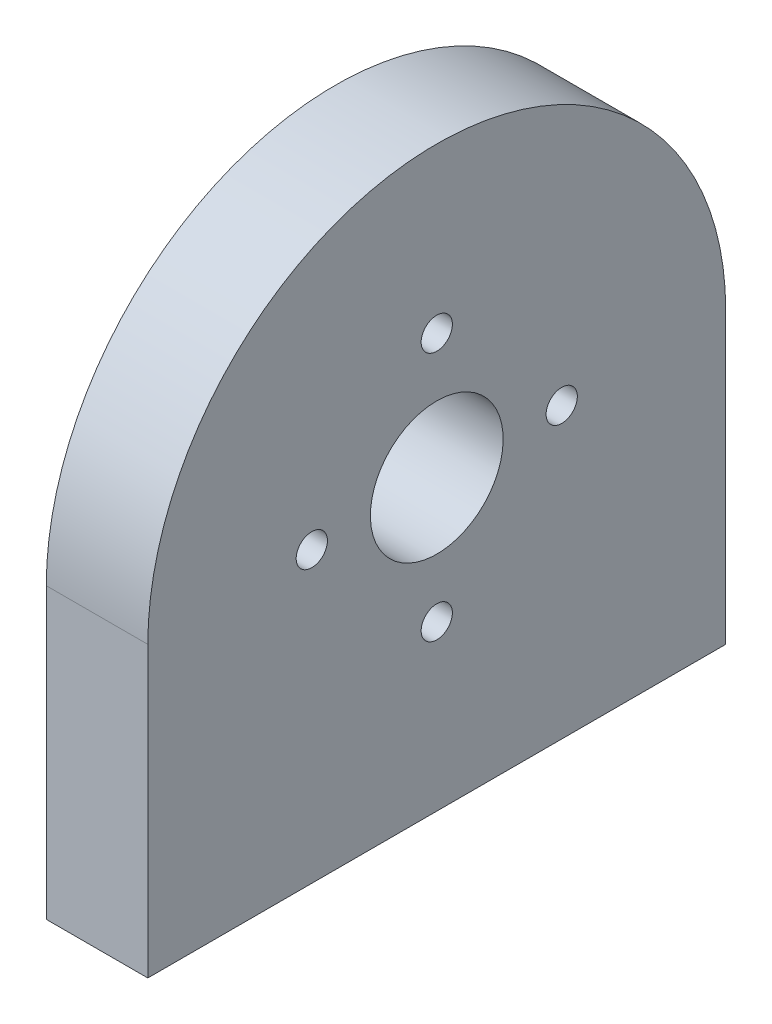
SolidWorks part; units mm, degrees
ref_plane "Front Plane" through (0, 0, 0) normal (0, 0, 1) x (1, 0, 0)
ref_plane "Top Plane" through (0, 0, 0) normal (0, 1, 0) x (1, 0, 0)
ref_plane "Right Plane" through (0, 0, 0) normal (1, 0, 0) x (0, 0, -1)
sketch "Sketch1" plane through (0, 0, 0) normal (0, 0, 1) x (1, 0, 0)
  line L1 (-25, 0) -> (25, 0)
  line L2 (-25, 0) -> (-25, -150)
  line L3 (-25, -150) -> (25, -150)
  line L4 (25, 0) -> (25, -150)
  dimension "D1" = 50
  dimension "D2" = 150
extrude "Boss-Extrude1" add sketch "Sketch1" against normal blind 55
sketch "Sketch2" plane through (25, 0, 0) normal (1, 0, 0) x (0, 0, -1)
  line L0 (55, 0) -> (0, 0) construction
  line L1 (0, -150) -> (0, 0) construction
  circle A0 centre (27.5, -25) radius 10.25
  dimension "D1" = 25
  dimension "D2" = 27.5
extrude "Cut-Extrude1" cut sketch "Sketch2" against normal blind 45 and the other way through all
sketch "Sketch7" plane through (-20, 0, 0) normal (1, 0, 0) x (0, 0, -1)
  line L0 (27.5, -17) -> (27.5, -33) construction
  circle A0 centre (27.5, -25) radius 8
  circle A1 centre (27.5, -17) radius 1
  circle A2 centre (35.5, -25) radius 1
  circle A3 centre (27.5, -33) radius 1
  circle A4 centre (19.5, -25) radius 1
  circle A5 centre (27.5, -25) radius 4.25
  point P14 (27.5, -25)
  dimension "D1" = 16
  dimension "D2" = 2
  dimension "D4" = 8.5
  dimension "D3" = 4
extrude "Cut-Extrude3" cut sketch "Sketch7" against normal blind 10 contours L0 A0 A1 | A0 A1 | A0 L0 A1 | A0 A4 | A0 A4 | L0 A3 A0 | A3 L0 A0 | A0 A3 | A0 A2 | A0 A2 | A5 L0 | L0 A5
sketch "Sketch8" plane through (25, 0, 0) normal (1, 0, 0) x (0, 0, -1)
  line L1 (55, -150) -> (55, 0) construction
  line L3 (0, -150) -> (55, -150)
  line L4 (0, -150) -> (0, -205)
  line L5 (0, -205) -> (55, -205)
  line L6 (55, -150) -> (55, -205)
  circle A1 centre (27.5, -180) radius 10.25
  circle A3 centre (27.5, -25) radius 10.25 construction
  dimension "D1" = 27.5
  dimension "D2" = 155
  dimension "D3" = 25
extrude "Boss-Extrude2" add sketch "Sketch8" against normal blind 50
sketch "Sketch10" plane through (0, 0, 0) normal (0, 0, 1) x (1, 0, 0)
  line L0 (-25, -205) -> (25, -205) construction
  line L5 (17, -205) -> (-17, -205)
  line L6 (17, -205) -> (17, -144.75)
  line L8 (-17, -205) -> (-17, -144.75)
  line L9 (-25, 0) -> (-25, -205) construction
  line L10 (-25, -180) -> (25, -180)
  line L13 (25, -169.75) -> (-25, -169.75)
  line L14 (25, -169.75) -> (25, -190.25)
  line L15 (25, -190.25) -> (-25, -190.25)
  line L16 (-25, -169.75) -> (-25, -190.25)
  line L17 (25, -205) -> (25, 0) construction
  line L18 (0, -180) -> (17, -180)
  line L19 (0, -180) -> (0, -191.25)
  line L20 (0, -191.25) -> (17, -191.25)
  line L21 (17, -180) -> (17, -191.25)
  line L22 (17, -191.25) -> (-17, -191.25)
  line L23 (17, -191.25) -> (17, -169.75)
  line L24 (17, -169.75) -> (-17, -169.75)
  line L25 (-17, -191.25) -> (-17, -169.75)
  line L26 (17, -191.25) -> (-17, -191.25)
  line L27 (17, -191.25) -> (17, -144.75)
  line L28 (17, -144.75) -> (-17, -144.75)
  line L29 (-17, -191.25) -> (-17, -144.75)
  line L30 (-25, -169.75) -> (-17, -169.75)
  line L31 (-25, -169.75) -> (-25, -205)
  line L32 (-25, -205) -> (-17, -205)
  line L33 (-17, -169.75) -> (-17, -205)
  line L34 (25, -169.75) -> (17, -169.75)
  line L35 (25, -169.75) -> (25, -205)
  line L36 (25, -205) -> (17, -205)
  line L37 (17, -169.75) -> (17, -205)
  line L38 (-25, -169.75) -> (25, -169.75)
  line L39 (-25, -169.75) -> (-25, -164.75)
  line L40 (-25, -164.75) -> (25, -164.75)
  line L41 (25, -169.75) -> (25, -164.75)
  line M7 (-25, 0) -> (-25, -205)
  line M8 (-25, -205) -> (25, -205)
  line M9 (25, -205) -> (25, 0)
  dimension "D1" = 8
  dimension "D2" = 8
  dimension "D3" = 11.25
  dimension "D4" = 46.5
  dimension "D5" = 60.25
  dimension "D6" = 5
extrude "Cut-Extrude4" cut sketch "Sketch10" against normal through all contours L20 L22 L8 L6 M8 | L8 L15 M7 M8 | L15 L6 M9 M8 | L15 L8 L10 M7 | L8 L13 L10 M7 | L13 L6 L10 M9 | L15 L10 L6 M9 | L19 L10 L8 L15 | L10 L19 L15 L6 | L6 L13 L8 L10 | L22 L19 L15 L8 | L19 L20 L6 L15 | L29 L40 L27 L28 | L40 L8 L13 L6
sketch "Sketch11" plane through (0, -144.75, 0) normal (0, -1, 0) x (1, 0, 0)
  line L0 (17, -55) -> (17, 0) construction
  line L1 (-17, 0) -> (17, 0)
  line L2 (-17, 0) -> (-17, -13.25)
  line L3 (-17, -13.25) -> (17, -13.25)
  line L4 (17, 0) -> (17, -13.25)
  line L5 (25, -27.5) -> (-30.9131, -27.5) construction
  line L6 (25, -55) -> (25, 0) construction
  line L7 (17, -55) -> (17, -41.75)
  line L8 (-17, -41.75) -> (17, -41.75)
  line L9 (-17, -55) -> (-17, -41.75)
  line L10 (-17, -55) -> (17, -55)
  dimension "D1" = 14.25
extrude "Boss-Extrude4" add sketch "Sketch11" along normal blind 25
sketch "Sketch13" plane through (25, 0, 0) normal (1, 0, 0) x (0, 0, -1)
  line L0 (0, -169.75) -> (0, 0) construction
  line L1 (55, -169.75) -> (0, -169.75)
  line L2 (55, -169.75) -> (55, -159.75)
  line L3 (55, -159.75) -> (0, -159.75)
  line L4 (0, -169.75) -> (0, -159.75)
  dimension "D1" = 10
extrude "Cut-Extrude5" cut sketch "Sketch13" against normal blind 8
ref_plane "Plane2" through (0, 0, 0) normal (1, 0, 0) x (0, 0, -1)
mirror "Mirror2" about plane through (0, 0, 0) normal (1, 0, 0) of "Cut-Extrude5"
sketch "Sketch14" plane through (25, 0, 0) normal (1, 0, 0) x (0, 0, -1)
  line L0 (55, -159.75) -> (0, -159.75) construction
  line L1 (0, -159.75) -> (0, 0) construction
  circle A1 centre (16.5, -148) radius 5.0302
  circle A2 centre (38.5, -148) radius 5.0302
  dimension "D1" = 16.5
  dimension "D2" = 2
  dimension "D3" = 11.75
extrude "Cut-Extrude6" cut sketch "Sketch14" against normal blind 8
mirror "Mirror3" about plane through (0, 0, 0) normal (1, 0, 0) of "Cut-Extrude6"
sketch "Sketch15" plane through (0, 0, 0) normal (0, 0, 1) x (1, 0, 0)
  line L0 (-25, 0) -> (25, 0)
  line L1 (25, 0) -> (0, 0)
  line L3 (-17, -169.75) -> (17, -169.75)
  line L4 (-17, -169.75) -> (-17, -170)
  line L5 (-17, -170) -> (17, -170)
  line L6 (17, -169.75) -> (17, -170)
  line M5 (-17, -169.75) -> (17, -169.75)
  dimension "D1" = 0.25
extrude "Boss-Extrude5" add sketch "Sketch15" against normal blind 13.25 contours L6 L4 L5 M5
ref_plane "Plane3" through (0, 0, -27.5) normal (0, 0, 1) x (1, 0, 0)
mirror "Mirror4" about plane through (0, 0, -27.5) normal (0, 0, 1) of "Boss-Extrude5"
sketch "Sketch16" plane through (0, 0, 0) normal (0, 0, 1) x (1, 0, 0)
  line L7 (-20, -14.75) -> (-18.5, -14.75)
  line L8 (-20, -14.75) -> (-20, -35.25)
  line L9 (-20, -35.25) -> (-18.5, -35.25)
  line L10 (-18.5, -14.75) -> (-18.5, -35.25)
  line L11 (25, 0) -> (-18.5, 0)
  line L12 (25, 0) -> (25, -43.5)
  line L13 (25, -43.5) -> (-18.5, -43.5)
  line L14 (-18.5, 0) -> (-18.5, -43.5)
  line M12 (25, -159.75) -> (25, 0)
  line M13 (25, 0) -> (-25, 0)
  dimension "D1" = 1.5
  dimension "D2" = 43.5
  dimension "D3" = 43.5
extrude "Cut-Extrude7" cut sketch "Sketch16" against normal through all contours L14 L10 L13 M13 M12
sketch "Sketch19" plane through (-20, 0, 0) normal (1, 0, 0) x (0, 0, -1)
  circle A0 centre (27.5, -25) radius 4.25
  circle A1 centre (35.5, -25) radius 1
  circle A2 centre (27.5, -33) radius 1
  circle A3 centre (19.5, -25) radius 1
  circle A4 centre (27.5, -17) radius 1
  point P15 (27.5, -25)
  circle M5 centre (27.5, -25) radius 4.25
  circle M6 centre (27.5, -17) radius 1
  circle M7 centre (35.5, -25) radius 1
  circle M8 centre (27.5, -33) radius 1
  circle M9 centre (19.5, -25) radius 1
  circle M10 centre (27.5, -25) radius 10.25
  dimension "D1" = 4
extrude "Boss-Extrude6" add sketch "Sketch19" along normal blind 1.5 contours M10 M6 M8 M9 M7 M5
sketch "Sketch20" plane through (-18.5, 0, 0) normal (1, 0, 0) x (0, 0, -1)
  line L0 (0, -43.5) -> (9, -43.5)
  line L1 (9, -25) -> (9, -43.5)
  line L2 (9, -43.5) -> (0, -43.5)
  line L3 (46, -25) -> (46, -43.5)
  line L4 (46, -43.5) -> (55, -43.5)
  line L5 (46, -43.5) -> (55, -43.5)
  line L7 (9, -43.5) -> (0, -43.5)
  line L8 (9, -43.5) -> (9, -25)
  line L12 (9, -25) -> (9, -43.5)
  line L13 (9, -43.5) -> (0, -43.5)
  line L15 (0, 0) -> (55, 0)
  line L16 (0, 0) -> (0, -43.5)
  line L17 (0, -43.5) -> (55, -43.5)
  line L18 (55, 0) -> (55, -43.5)
  circle A0 centre (27.5, -25) radius 18.5
  line M6 (0, 0) -> (0, -43.5)
  line M7 (0, -43.5) -> (55, -43.5)
  line M8 (55, -43.5) -> (55, 0)
  line M9 (55, 0) -> (0, 0)
extrude "Cut-Extrude8" cut sketch "Sketch20" against normal through all contours A0 L3 L1 M7 M8 M9 M6
sketch "Sketch21" plane through (25, 0, 0) normal (1, 0, 0) x (0, 0, -1)
  circle A0 centre (16.5, -148) radius 5.0302
  circle A1 centre (16.5, -148) radius 4.5
  circle A2 centre (38.5, -148) radius 4.5
  circle A3 centre (38.5, -148) radius 5.0302
  dimension "D1" = 2
extrude "Boss-Extrude7" add sketch "Sketch21" against normal blind 8
mirror "Mirror5" about plane through (0, 0, 0) normal (1, 0, 0) of "Boss-Extrude7"
sketch "Sketch24" plane through (0, 0, 0) normal (0, 0, 1) x (1, 0, 0)
  line L1 (-25, -159.75) -> (-21, -159.75)
  line L2 (-25, -159.75) -> (-25, -129.75)
  line L3 (-25, -129.75) -> (-21, -129.75)
  line L4 (-21, -159.75) -> (-21, -129.75)
  line L5 (25, -159.75) -> (21, -159.75)
  line L6 (25, -159.75) -> (25, -129.75)
  line L7 (25, -129.75) -> (21, -129.75)
  line L8 (21, -159.75) -> (21, -129.75)
  dimension "D1" = 30
  dimension "D2" = 30
  dimension "D3" = 4
  dimension "D4" = 4
extrude "Cut-Extrude10" cut sketch "Sketch24" against normal through all
sketch "Sketch25" plane through (25, 0, 0) normal (1, 0, 0) x (0, 0, -1)
  line L1 (0, -43.5) -> (55, -43.5)
  line L2 (0, -43.5) -> (0, -129.75)
  line L3 (0, -129.75) -> (55, -129.75)
  line L4 (55, -43.5) -> (55, -129.75)
extrude "Cut-Extrude11" cut sketch "Sketch25" against normal blind 4
sketch "Sketch26" plane through (-18.5, 0, 0) normal (1, 0, 0) x (0, 0, -1)
  line L1 (46, -43.5) -> (9, -43.5)
  line L2 (46, -43.5) -> (46, -25)
  line L3 (46, -25) -> (9, -25)
  line L4 (9, -43.5) -> (9, -25)
  circle A0 centre (27.5, -25) radius 18.5
  circle A1 centre (27.5, -25) radius 4.25
  circle A2 centre (27.5, -33) radius 1
  circle A3 centre (35.5, -25) radius 1
  circle A4 centre (27.5, -17) radius 1
  circle A5 centre (19.5, -25) radius 1
  circle M1 centre (27.5, -25) radius 4.25
  circle M2 centre (35.5, -25) radius 1
  circle M3 centre (19.5, -25) radius 1
  circle M4 centre (27.5, -33) radius 1
  circle M5 centre (27.5, -17) radius 1
  line M6 (9, -25) -> (9, -43.5)
  line M7 (9, -43.5) -> (46, -43.5)
  line M8 (46, -43.5) -> (46, -25)
  arc M9 (46, -25) -> (9, -25) centre (27.5, -25) ccw
extrude "Boss-Extrude8" add sketch "Sketch26" along normal blind 4 contours A0 M6 M7 | A0 L1 M8 | L3 A0 M2 M1 M3 M4 | L3 M9 M3 M1 M2 M5
sketch "Sketch27" plane through (0, 0, 0) normal (0, 0, 1) x (1, 0, 0)
  line L1 (-21, -129.75) -> (-25, -129.75)
  line L2 (-21, -129.75) -> (-21, -6.5)
  line L3 (-21, -6.5) -> (-25, -6.5)
  line L4 (-25, -129.75) -> (-25, -6.5)
extrude "Cut-Extrude12" cut sketch "Sketch27" against normal through all
sketch "Sketch28" plane through (0, 0, 0) normal (0, 0, 1) x (1, 0, 0)
  line L1 (-14.5, -43.5) -> (-21, -43.5)
  line L2 (21, -79) -> (21, -159.75)
  line L3 (21, -159.75) -> (-21, -159.75)
  line L4 (-21, -43.5) -> (-21, -159.75)
  line L5 (21, -43.5) -> (-21, -43.5)
  line L6 (21, -43.5) -> (21, -159.75)
  line L7 (21, -159.75) -> (-21, -159.75)
  line L8 (-21, -43.5) -> (-21, -159.75)
  arc A0 (21, -79) -> (-14.5, -43.5) centre (-14.5, -79) ccw
  point P8 (21, -43.5)
  line M2 (21, -43.5) -> (-21, -43.5)
  line M9 (21, -159.75) -> (21, -43.5)
  dimension "D1" = 35.5
extrude "Cut-Extrude13" cut sketch "Sketch28" against normal through all contours A0 M9 M2
sketch "Sketch29" plane through (0, -170, 0) normal (0, -1, 0) x (1, 0, 0)
  line L5 (-21, -55) -> (-21, 0) construction
  line L6 (21, -55) -> (-21, -55)
  line L7 (21, -55) -> (21, -46)
  line L8 (21, -46) -> (-21, -46)
  line L9 (-21, -55) -> (-21, -46)
  line L10 (21, -55) -> (21, 0) construction
  line L11 (-21, 0) -> (21, 0)
  line L12 (-21, 0) -> (-21, -9)
  line L13 (-21, -9) -> (21, -9)
  line L14 (21, 0) -> (21, -9)
  dimension "D1" = 9
  dimension "D2" = 9
extrude "Cut-Extrude15" cut sketch "Sketch29" against normal through all
sketch "Sketch30" plane through (21, 0, 0) normal (1, 0, 0) x (0, 0, -1)
  circle A0 centre (16.5, -148) radius 4.5
  circle A1 centre (38.5, -148) radius 4.5
  circle A2 centre (16.5, -148) radius 1.45
  circle A3 centre (38.5, -148) radius 1.45
extrude "Boss-Extrude9" add sketch "Sketch30" against normal blind 4
mirror "Mirror6" about plane through (0, 0, 0) normal (1, 0, 0) of "Boss-Extrude9"
sketch "Sketch31" plane through (-21, 0, 0) normal (-1, 0, 0) x (0, 0, 1)
  line L0 (-9, -159.75) -> (-9, -25) construction
  line L1 (-46, -43.5) -> (-9, -43.5)
  line L2 (-46, -43.5) -> (-46, -98.5)
  line L3 (-46, -98.5) -> (-9, -98.5)
  line L4 (-9, -43.5) -> (-9, -98.5)
  dimension "D1" = 55
extrude "Cut-Extrude16" cut sketch "Sketch31" against normal through all
sketch "Sketch32" plane through (-21, 0, 0) normal (-1, 0, 0) x (0, 0, 1)
  line L1 (-65.8177, -83.1561) -> (8.1506, -83.1561)
  line L2 (-65.8177, -83.1561) -> (-65.8177, -175.3794)
  line L3 (-65.8177, -175.3794) -> (8.1506, -175.3794)
  line L4 (8.1506, -83.1561) -> (8.1506, -175.3794)
extrude "Cut-Extrude17" cut sketch "Sketch32" against normal through all
